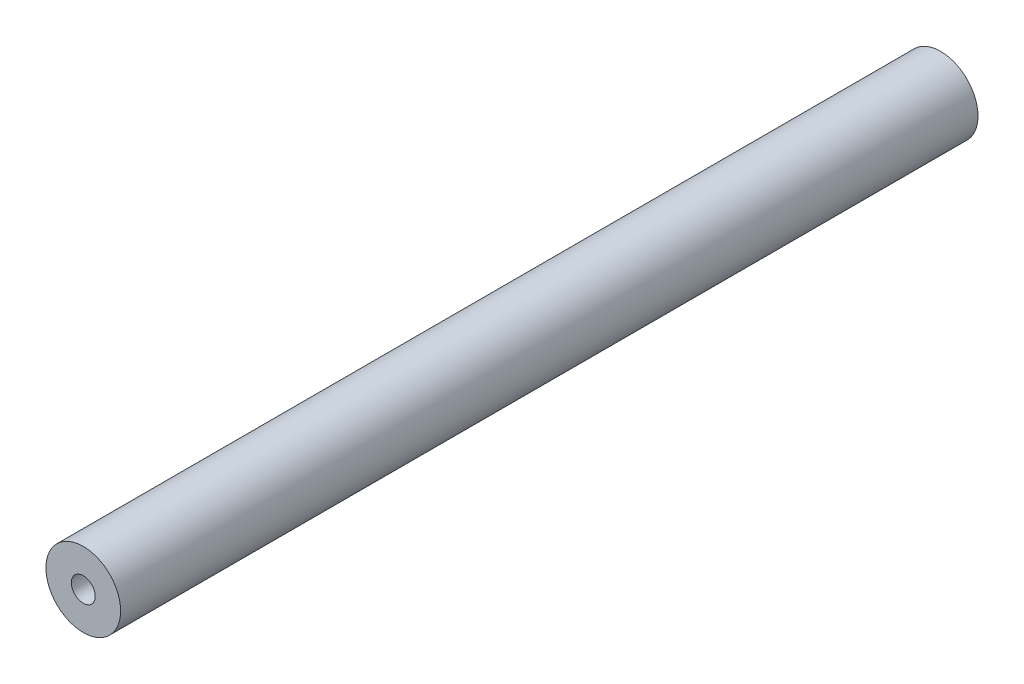
SolidWorks part; units mm, degrees
ref_plane "Front Plane" through (0, 0, 0) normal (0, 0, 1) x (1, 0, 0)
ref_plane "Top Plane" through (0, 0, 0) normal (0, 1, 0) x (1, 0, 0)
ref_plane "Right Plane" through (0, 0, 0) normal (1, 0, 0) x (0, 0, -1)
sketch "Sketch1" plane through (0, 0, 0) normal (0, 0, 1) x (1, 0, 0)
  circle A0 centre (0, 0) radius 12.5
extrude "Boss-Extrude1" add sketch "Sketch1" along normal blind 287
sketch "Sketch2" plane through (0, 0, 0) normal (0, 0, 1) x (1, 0, 0)
  circle A0 centre (0, 0) radius 4
extrude "Cut-Extrude1" cut sketch "Sketch2" along normal blind 395
